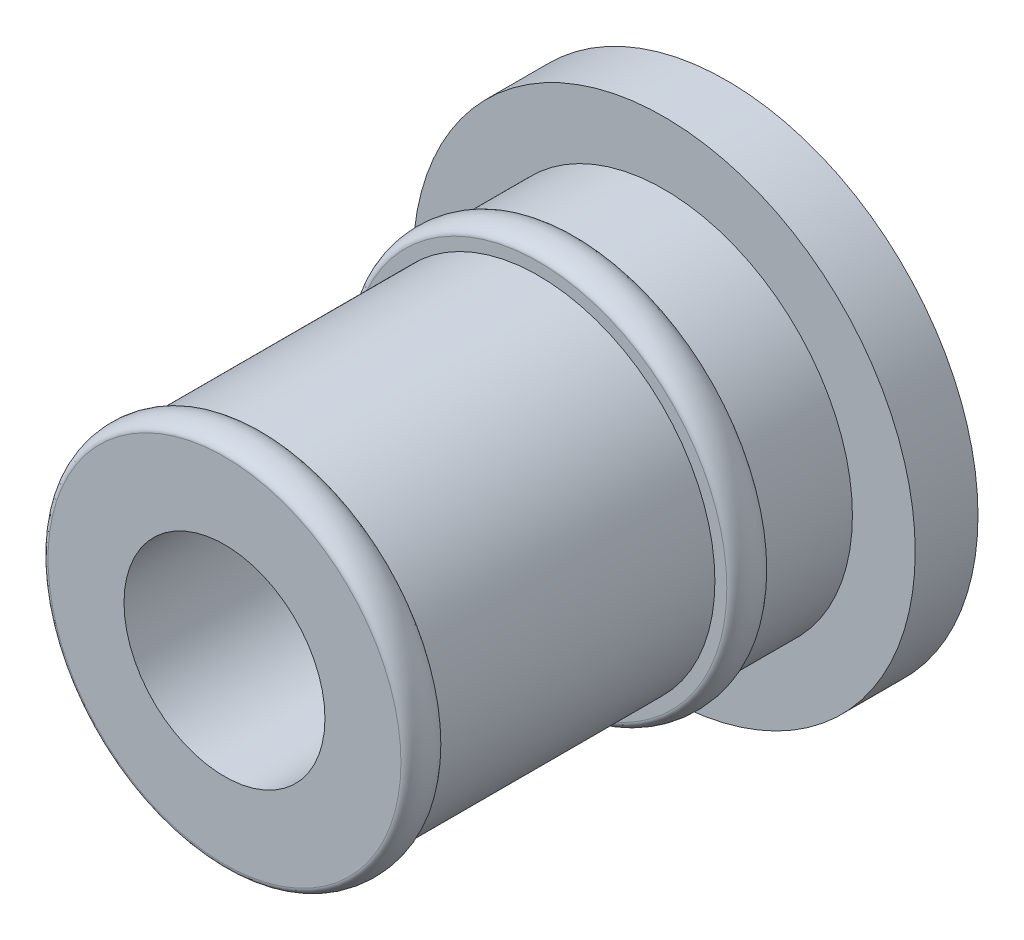
SolidWorks part; units mm, degrees
ref_plane "Front Plane" through (0, 0, 0) normal (0, 0, 1) x (1, 0, 0)
ref_plane "Top Plane" through (0, 0, 0) normal (0, 1, 0) x (1, 0, 0)
ref_plane "Right Plane" through (0, 0, 0) normal (1, 0, 0) x (0, 0, -1)
sketch "Sketch1" plane through (0, 0, 0) normal (0, 0, 1) x (1, 0, 0)
  circle A0 centre (0, 0) radius 4
  circle A1 centre (0, 0) radius 1.6
extrude "Boss-Extrude1" add sketch "Sketch1" along normal blind 8
sketch "Sketch2" plane through (0, 0, 0) normal (1, 0, 0) x (0, 0, -1)
  line L0 (-8, 0) -> (0, 0) construction
  line L7 (-2.4, 3) -> (-1, 3)
  line L8 (-8, 4) -> (-1, 4)
  line L11 (-1, 4) -> (-1, 3)
  line L12 (-7.4, 2.81) -> (-3, 2.81)
  line L13 (-3, 2.81) -> (-3, 3)
  line L14 (-8, 2.81) -> (-8, 4)
  ellipse E0 centre (-2.7, 3) end of major axis (-2.4, 3) minor radius 0.15 (-2.4, 3) -> (-3, 3) ccw
  ellipse E1 centre (-7.7, 2.81) end of major axis (-7.4, 2.81) minor radius 0.15 (-7.4, 2.81) -> (-8, 2.81) ccw
revolve "Cut-Revolve1" cut sketch "Sketch2" angle 360 about L0
